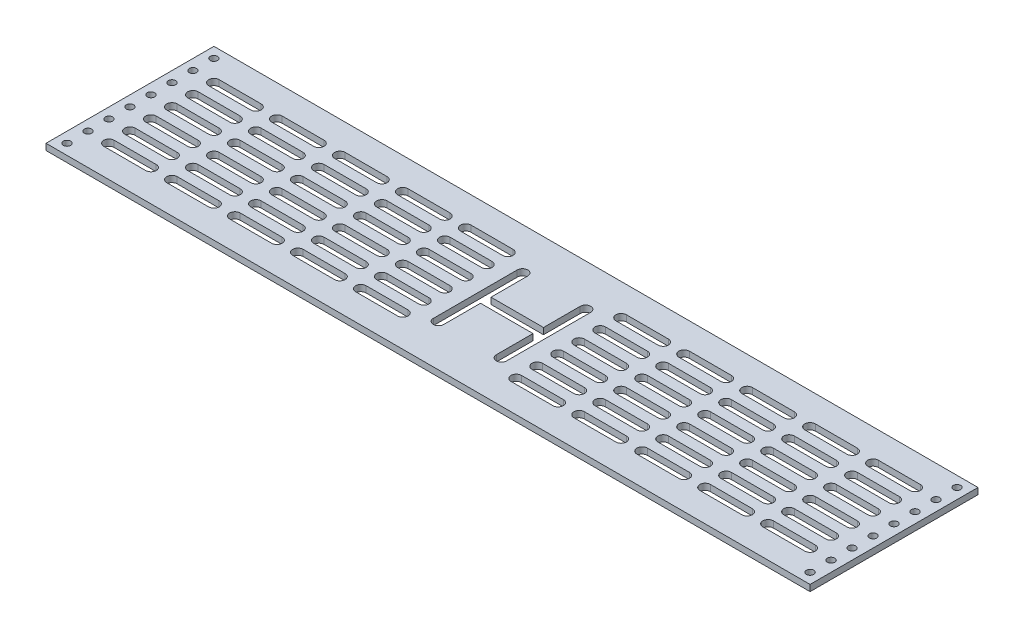
SolidWorks part; units mm, degrees
material "A-玻璃纤维"
ref_plane "前视基准面" through (0, 0, 0) normal (0, 0, 1) x (1, 0, 0)
ref_plane "上视基准面" through (0, 0, 0) normal (0, 1, 0) x (1, 0, 0)
ref_plane "右视基准面" through (0, 0, 0) normal (1, 0, 0) x (0, 0, -1)
other "Configuration Table"
sketch "草图1" plane through (0, 0, 0) normal (0, 1, 0) x (1, 0, 0)
  line L0 (0, 0) -> (-182, 0)
  line L1 (0, 0) -> (182, 0)
  line L2 (182, 0) -> (182, -80)
  line L3 (182, -80) -> (-182, -80)
  line L4 (-182, -80) -> (-182, 0)
extrude "凸台-拉伸1" add sketch "草图1" along normal blind 3
sketch "草图2" plane through (0, 3, 0) normal (0, 1, 0) x (1, 0, 0)
  line L0 (-182, -80) -> (-177, -80)
  line L1 (-182, -80) -> (182, -80) construction
  line L2 (-177, -80) -> (-177, 0)
  line L3 (182, 0) -> (-182, 0) construction
  line L4 (-177, -80) -> (-177, -75)
  line L5 (0, 0) -> (0, -80)
  circle A0 centre (-177, -75) radius 1.75
  circle A1 centre (-177, -65) radius 1.75
  circle A2 centre (-177, -55) radius 1.75
  circle A3 centre (-177, -45) radius 1.75
  circle A4 centre (-177, -35) radius 1.75
  circle A5 centre (-177, -25) radius 1.75
  circle A6 centre (-177, -15) radius 1.75
  circle A7 centre (-177, -5) radius 1.75
  circle A8 centre (177, -5) radius 1.75
  circle A9 centre (177, -15) radius 1.75
  circle A10 centre (177, -25) radius 1.75
  circle A11 centre (177, -35) radius 1.75
  circle A12 centre (177, -45) radius 1.75
  circle A13 centre (177, -55) radius 1.75
  circle A14 centre (177, -65) radius 1.75
  circle A15 centre (177, -75) radius 1.75
  dimension "D1" = 8
  dimension "D2" = 3.5
  dimension "D3" = 5
extrude "切除-拉伸1" cut sketch "草图2" against normal through all contours L4 A0 L2 | L2 A0 L4 | L2 A1 | L2 A1 | L2 A2 | L2 A2 | L2 A3 | L2 A3 | L2 A4 | L2 A4 | L2 A5 | L2 A5 | L2 A6 | L2 A6 | L2 A7 | L2 A7 | A8 | A9 | A10 | A11 | A12 | A13 | A14 | A15
sketch "草图3" plane through (0, 3, 0) normal (0, 1, 0) x (1, 0, 0)
  line L0 (0, 0) -> (0, -80)
  line L1 (182, 0) -> (-182, 0) construction
  line L2 (-182, -80) -> (182, -80) construction
  line L3 (0, -40) -> (-15, -40)
  line L4 (0, -40) -> (15, -40)
  line L5 (15, -40) -> (15, -20)
  line L6 (15, -40) -> (15, -60)
  line L7 (-15, -40) -> (-15, -20)
  line L8 (-15, -40) -> (-15, -60)
  line L9 (-15, -40) -> (15, -40) construction
  line L10 (-12.5, -37.5) -> (12.5, -37.5)
  line L11 (-12.5, -42.5) -> (12.5, -42.5)
  line L12 (-15, -20) -> (-15, -60) construction
  line L13 (-12.5, -20) -> (-12.5, -37.5)
  line L14 (-17.5, -20) -> (-17.5, -60)
  line L15 (15, -20) -> (15, -60) construction
  line L16 (17.5, -20) -> (17.5, -60)
  line L17 (12.5, -20) -> (12.5, -37.5)
  line L18 (12.5, -42.5) -> (12.5, -60)
  line L19 (-12.5, -42.5) -> (-12.5, -60)
  line L20 (-182, -80) -> (0, -80)
  line L21 (-91, -80) -> (-91, 0)
  line L22 (-177, -65) -> (-91, -65)
  line L23 (-177, -65) -> (-167, -65)
  line L24 (-167, -65) -> (-147, -65)
  line L25 (-147, -65) -> (-137, -65)
  line L26 (-137, -65) -> (-117, -65)
  line L27 (-117, -65) -> (-107, -65)
  line L28 (-107, -65) -> (-87, -65)
  line L29 (-87, -65) -> (-77, -65)
  line L30 (-77, -65) -> (-57, -65)
  line L31 (-167, -65) -> (-147, -65) construction
  line L32 (-167, -62.5) -> (-147, -62.5)
  line L33 (-167, -67.5) -> (-147, -67.5)
  line L34 (-137, -65) -> (-117, -65) construction
  line L35 (-137, -62.5) -> (-117, -62.5)
  line L36 (-137, -67.5) -> (-117, -67.5)
  line L37 (-107, -65) -> (-87, -65) construction
  line L38 (-107, -62.5) -> (-87, -62.5)
  line L39 (-107, -67.5) -> (-87, -67.5)
  line L40 (-77, -65) -> (-57, -65) construction
  line L41 (-77, -62.5) -> (-57, -62.5)
  line L42 (-77, -67.5) -> (-57, -67.5)
  line L43 (-167, -57.5) -> (-147, -57.5)
  line L44 (-167, -52.5) -> (-147, -52.5)
  line L45 (-137, -57.5) -> (-117, -57.5)
  line L46 (-137, -52.5) -> (-117, -52.5)
  line L47 (-107, -57.5) -> (-87, -57.5)
  line L48 (-107, -52.5) -> (-87, -52.5)
  line L49 (-77, -57.5) -> (-57, -57.5)
  line L50 (-77, -52.5) -> (-57, -52.5)
  line L51 (-167, -55) -> (-147, -55) construction
  line L52 (-137, -55) -> (-117, -55) construction
  line L53 (-107, -55) -> (-87, -55) construction
  line L54 (-77, -55) -> (-57, -55) construction
  line L55 (-167, -47.5) -> (-147, -47.5)
  line L56 (-167, -42.5) -> (-147, -42.5)
  line L57 (-137, -47.5) -> (-117, -47.5)
  line L58 (-137, -42.5) -> (-117, -42.5)
  line L59 (-107, -47.5) -> (-87, -47.5)
  line L60 (-107, -42.5) -> (-87, -42.5)
  line L61 (-77, -47.5) -> (-57, -47.5)
  line L62 (-77, -42.5) -> (-57, -42.5)
  line L63 (-167, -45) -> (-147, -45) construction
  line L64 (-137, -45) -> (-117, -45) construction
  line L65 (-107, -45) -> (-87, -45) construction
  line L66 (-77, -45) -> (-57, -45) construction
  line L67 (-167, -37.5) -> (-147, -37.5)
  line L68 (-167, -32.5) -> (-147, -32.5)
  line L69 (-137, -37.5) -> (-117, -37.5)
  line L70 (-137, -32.5) -> (-117, -32.5)
  line L71 (-107, -37.5) -> (-87, -37.5)
  line L72 (-107, -32.5) -> (-87, -32.5)
  line L73 (-77, -37.5) -> (-57, -37.5)
  line L74 (-77, -32.5) -> (-57, -32.5)
  line L75 (-167, -35) -> (-147, -35) construction
  line L76 (-137, -35) -> (-117, -35) construction
  line L77 (-107, -35) -> (-87, -35) construction
  line L78 (-77, -35) -> (-57, -35) construction
  line L79 (-167, -27.5) -> (-147, -27.5)
  line L80 (-167, -22.5) -> (-147, -22.5)
  line L81 (-137, -27.5) -> (-117, -27.5)
  line L82 (-137, -22.5) -> (-117, -22.5)
  line L83 (-107, -27.5) -> (-87, -27.5)
  line L84 (-107, -22.5) -> (-87, -22.5)
  line L85 (-77, -27.5) -> (-57, -27.5)
  line L86 (-77, -22.5) -> (-57, -22.5)
  line L87 (-167, -25) -> (-147, -25) construction
  line L88 (-137, -25) -> (-117, -25) construction
  line L89 (-107, -25) -> (-87, -25) construction
  line L90 (-77, -25) -> (-57, -25) construction
  line L91 (-167, -17.5) -> (-147, -17.5)
  line L92 (-167, -12.5) -> (-147, -12.5)
  line L93 (-137, -17.5) -> (-117, -17.5)
  line L94 (-137, -12.5) -> (-117, -12.5)
  line L95 (-107, -17.5) -> (-87, -17.5)
  line L96 (-107, -12.5) -> (-87, -12.5)
  line L97 (-77, -17.5) -> (-57, -17.5)
  line L98 (-77, -12.5) -> (-57, -12.5)
  line L99 (-167, -15) -> (-147, -15) construction
  line L100 (-137, -15) -> (-117, -15) construction
  line L101 (-107, -15) -> (-87, -15) construction
  line L102 (-77, -15) -> (-57, -15) construction
  line L103 (87, -65) -> (77, -65)
  line L104 (107, -65) -> (87, -65)
  line L105 (117, -65) -> (107, -65)
  line L106 (137, -65) -> (117, -65)
  line L107 (147, -65) -> (137, -65)
  line L108 (167, -65) -> (147, -65)
  line L109 (77, -15) -> (57, -15) construction
  line L110 (77, -12.5) -> (57, -12.5)
  line L111 (77, -17.5) -> (57, -17.5)
  line L112 (107, -15) -> (87, -15) construction
  line L113 (107, -12.5) -> (87, -12.5)
  line L114 (107, -17.5) -> (87, -17.5)
  line L115 (137, -15) -> (117, -15) construction
  line L116 (137, -12.5) -> (117, -12.5)
  line L117 (137, -17.5) -> (117, -17.5)
  line L118 (77, -25) -> (57, -25) construction
  line L119 (77, -22.5) -> (57, -22.5)
  line L120 (77, -27.5) -> (57, -27.5)
  line L121 (107, -25) -> (87, -25) construction
  line L122 (107, -22.5) -> (87, -22.5)
  line L123 (107, -27.5) -> (87, -27.5)
  line L124 (137, -25) -> (117, -25) construction
  line L125 (137, -22.5) -> (117, -22.5)
  line L126 (137, -27.5) -> (117, -27.5)
  line L127 (77, -35) -> (57, -35) construction
  line L128 (77, -32.5) -> (57, -32.5)
  line L129 (77, -37.5) -> (57, -37.5)
  line L130 (107, -35) -> (87, -35) construction
  line L131 (107, -32.5) -> (87, -32.5)
  line L132 (107, -37.5) -> (87, -37.5)
  line L133 (137, -35) -> (117, -35) construction
  line L134 (137, -32.5) -> (117, -32.5)
  line L135 (137, -37.5) -> (117, -37.5)
  line L136 (167, -35) -> (147, -35) construction
  line L137 (167, -32.5) -> (147, -32.5)
  line L138 (167, -37.5) -> (147, -37.5)
  line L139 (77, -45) -> (57, -45) construction
  line L140 (77, -42.5) -> (57, -42.5)
  line L141 (77, -47.5) -> (57, -47.5)
  line L142 (107, -45) -> (87, -45) construction
  line L143 (107, -42.5) -> (87, -42.5)
  line L144 (107, -47.5) -> (87, -47.5)
  line L145 (137, -45) -> (117, -45) construction
  line L146 (137, -42.5) -> (117, -42.5)
  line L147 (137, -47.5) -> (117, -47.5)
  line L148 (167, -45) -> (147, -45) construction
  line L149 (167, -42.5) -> (147, -42.5)
  line L150 (167, -47.5) -> (147, -47.5)
  line L151 (77, -55) -> (57, -55) construction
  line L152 (77, -52.5) -> (57, -52.5)
  line L153 (77, -57.5) -> (57, -57.5)
  line L154 (107, -55) -> (87, -55) construction
  line L155 (107, -52.5) -> (87, -52.5)
  line L156 (107, -57.5) -> (87, -57.5)
  line L157 (137, -55) -> (117, -55) construction
  line L158 (137, -52.5) -> (117, -52.5)
  line L159 (137, -57.5) -> (117, -57.5)
  line L160 (167, -55) -> (147, -55) construction
  line L161 (167, -52.5) -> (147, -52.5)
  line L162 (167, -57.5) -> (147, -57.5)
  line L163 (77, -65) -> (57, -65) construction
  line L164 (77, -62.5) -> (57, -62.5)
  line L165 (77, -67.5) -> (57, -67.5)
  line L166 (107, -65) -> (87, -65) construction
  line L167 (107, -62.5) -> (87, -62.5)
  line L168 (107, -67.5) -> (87, -67.5)
  line L169 (137, -65) -> (117, -65) construction
  line L170 (137, -62.5) -> (117, -62.5)
  line L171 (137, -67.5) -> (117, -67.5)
  line L172 (167, -65) -> (147, -65) construction
  line L173 (167, -62.5) -> (147, -62.5)
  line L174 (167, -67.5) -> (147, -67.5)
  line L175 (167, -25) -> (147, -25) construction
  line L176 (167, -22.5) -> (147, -22.5)
  line L177 (167, -27.5) -> (147, -27.5)
  line L178 (167, -15) -> (147, -15) construction
  line L179 (167, -12.5) -> (147, -12.5)
  line L180 (167, -17.5) -> (147, -17.5)
  line L181 (-57, -65) -> (-47, -65)
  line L182 (-47, -65) -> (-27, -65)
  line L183 (-47, -65) -> (-27, -65) construction
  line L184 (-47, -62.5) -> (-27, -62.5)
  line L185 (-47, -67.5) -> (-27, -67.5)
  line L186 (-47, -57.5) -> (-27, -57.5)
  line L187 (-47, -52.5) -> (-27, -52.5)
  line L188 (-47, -55) -> (-27, -55) construction
  line L189 (-47, -47.5) -> (-27, -47.5)
  line L190 (-47, -42.5) -> (-27, -42.5)
  line L191 (-47, -45) -> (-27, -45) construction
  line L192 (-47, -37.5) -> (-27, -37.5)
  line L193 (-47, -32.5) -> (-27, -32.5)
  line L194 (-47, -35) -> (-27, -35) construction
  line L195 (-47, -27.5) -> (-27, -27.5)
  line L196 (-47, -22.5) -> (-27, -22.5)
  line L197 (-47, -25) -> (-27, -25) construction
  line L198 (-47, -17.5) -> (-27, -17.5)
  line L199 (-47, -12.5) -> (-27, -12.5)
  line L200 (-47, -15) -> (-27, -15) construction
  line L201 (47, -65) -> (27, -65)
  line L202 (47, -15) -> (27, -15) construction
  line L203 (47, -12.5) -> (27, -12.5)
  line L204 (47, -17.5) -> (27, -17.5)
  line L205 (47, -25) -> (27, -25) construction
  line L206 (47, -22.5) -> (27, -22.5)
  line L207 (47, -27.5) -> (27, -27.5)
  line L208 (47, -35) -> (27, -35) construction
  line L209 (47, -32.5) -> (27, -32.5)
  line L210 (47, -37.5) -> (27, -37.5)
  line L211 (47, -45) -> (27, -45) construction
  line L212 (47, -42.5) -> (27, -42.5)
  line L213 (47, -47.5) -> (27, -47.5)
  line L214 (47, -55) -> (27, -55) construction
  line L215 (47, -52.5) -> (27, -52.5)
  line L216 (47, -57.5) -> (27, -57.5)
  line L217 (47, -65) -> (27, -65) construction
  line L218 (47, -62.5) -> (27, -62.5)
  line L219 (47, -67.5) -> (27, -67.5)
  arc A2 (-12.5, -20) -> (-17.5, -20) centre (-15, -20) ccw
  arc A3 (-17.5, -60) -> (-12.5, -60) centre (-15, -60) ccw
  arc A4 (17.5, -20) -> (12.5, -20) centre (15, -20) ccw
  arc A5 (12.5, -60) -> (17.5, -60) centre (15, -60) ccw
  arc A6 (-167, -62.5) -> (-167, -67.5) centre (-167, -65) ccw
  arc A7 (-147, -67.5) -> (-147, -62.5) centre (-147, -65) ccw
  arc A8 (-137, -62.5) -> (-137, -67.5) centre (-137, -65) ccw
  arc A9 (-117, -67.5) -> (-117, -62.5) centre (-117, -65) ccw
  arc A10 (-107, -62.5) -> (-107, -67.5) centre (-107, -65) ccw
  arc A11 (-87, -67.5) -> (-87, -62.5) centre (-87, -65) ccw
  arc A12 (-77, -62.5) -> (-77, -67.5) centre (-77, -65) ccw
  arc A13 (-57, -67.5) -> (-57, -62.5) centre (-57, -65) ccw
  arc A14 (-167, -52.5) -> (-167, -57.5) centre (-167, -55) ccw
  arc A15 (-147, -57.5) -> (-147, -52.5) centre (-147, -55) ccw
  arc A16 (-137, -52.5) -> (-137, -57.5) centre (-137, -55) ccw
  arc A17 (-117, -57.5) -> (-117, -52.5) centre (-117, -55) ccw
  arc A18 (-107, -52.5) -> (-107, -57.5) centre (-107, -55) ccw
  arc A19 (-87, -57.5) -> (-87, -52.5) centre (-87, -55) ccw
  arc A20 (-77, -52.5) -> (-77, -57.5) centre (-77, -55) ccw
  arc A21 (-57, -57.5) -> (-57, -52.5) centre (-57, -55) ccw
  arc A22 (-167, -42.5) -> (-167, -47.5) centre (-167, -45) ccw
  arc A23 (-147, -47.5) -> (-147, -42.5) centre (-147, -45) ccw
  arc A24 (-137, -42.5) -> (-137, -47.5) centre (-137, -45) ccw
  arc A25 (-117, -47.5) -> (-117, -42.5) centre (-117, -45) ccw
  arc A26 (-107, -42.5) -> (-107, -47.5) centre (-107, -45) ccw
  arc A27 (-87, -47.5) -> (-87, -42.5) centre (-87, -45) ccw
  arc A28 (-77, -42.5) -> (-77, -47.5) centre (-77, -45) ccw
  arc A29 (-57, -47.5) -> (-57, -42.5) centre (-57, -45) ccw
  arc A30 (-167, -32.5) -> (-167, -37.5) centre (-167, -35) ccw
  arc A31 (-147, -37.5) -> (-147, -32.5) centre (-147, -35) ccw
  arc A32 (-137, -32.5) -> (-137, -37.5) centre (-137, -35) ccw
  arc A33 (-117, -37.5) -> (-117, -32.5) centre (-117, -35) ccw
  arc A34 (-107, -32.5) -> (-107, -37.5) centre (-107, -35) ccw
  arc A35 (-87, -37.5) -> (-87, -32.5) centre (-87, -35) ccw
  arc A36 (-77, -32.5) -> (-77, -37.5) centre (-77, -35) ccw
  arc A37 (-57, -37.5) -> (-57, -32.5) centre (-57, -35) ccw
  arc A38 (-167, -22.5) -> (-167, -27.5) centre (-167, -25) ccw
  arc A39 (-147, -27.5) -> (-147, -22.5) centre (-147, -25) ccw
  arc A40 (-137, -22.5) -> (-137, -27.5) centre (-137, -25) ccw
  arc A41 (-117, -27.5) -> (-117, -22.5) centre (-117, -25) ccw
  arc A42 (-107, -22.5) -> (-107, -27.5) centre (-107, -25) ccw
  arc A43 (-87, -27.5) -> (-87, -22.5) centre (-87, -25) ccw
  arc A44 (-77, -22.5) -> (-77, -27.5) centre (-77, -25) ccw
  arc A45 (-57, -27.5) -> (-57, -22.5) centre (-57, -25) ccw
  arc A46 (-167, -12.5) -> (-167, -17.5) centre (-167, -15) ccw
  arc A47 (-147, -17.5) -> (-147, -12.5) centre (-147, -15) ccw
  arc A48 (-137, -12.5) -> (-137, -17.5) centre (-137, -15) ccw
  arc A49 (-117, -17.5) -> (-117, -12.5) centre (-117, -15) ccw
  arc A50 (-107, -12.5) -> (-107, -17.5) centre (-107, -15) ccw
  arc A51 (-87, -17.5) -> (-87, -12.5) centre (-87, -15) ccw
  arc A52 (-77, -12.5) -> (-77, -17.5) centre (-77, -15) ccw
  arc A53 (-57, -17.5) -> (-57, -12.5) centre (-57, -15) ccw
  arc A54 (77, -12.5) -> (77, -17.5) centre (77, -15) cw
  arc A55 (57, -17.5) -> (57, -12.5) centre (57, -15) cw
  arc A56 (107, -12.5) -> (107, -17.5) centre (107, -15) cw
  arc A57 (87, -17.5) -> (87, -12.5) centre (87, -15) cw
  arc A58 (137, -12.5) -> (137, -17.5) centre (137, -15) cw
  arc A59 (117, -17.5) -> (117, -12.5) centre (117, -15) cw
  arc A60 (77, -22.5) -> (77, -27.5) centre (77, -25) cw
  arc A61 (57, -27.5) -> (57, -22.5) centre (57, -25) cw
  arc A62 (107, -22.5) -> (107, -27.5) centre (107, -25) cw
  arc A63 (87, -27.5) -> (87, -22.5) centre (87, -25) cw
  arc A64 (137, -22.5) -> (137, -27.5) centre (137, -25) cw
  arc A65 (117, -27.5) -> (117, -22.5) centre (117, -25) cw
  arc A66 (77, -32.5) -> (77, -37.5) centre (77, -35) cw
  arc A67 (57, -37.5) -> (57, -32.5) centre (57, -35) cw
  arc A68 (107, -32.5) -> (107, -37.5) centre (107, -35) cw
  arc A69 (87, -37.5) -> (87, -32.5) centre (87, -35) cw
  arc A70 (137, -32.5) -> (137, -37.5) centre (137, -35) cw
  arc A71 (117, -37.5) -> (117, -32.5) centre (117, -35) cw
  arc A72 (167, -32.5) -> (167, -37.5) centre (167, -35) cw
  arc A73 (147, -37.5) -> (147, -32.5) centre (147, -35) cw
  arc A74 (77, -42.5) -> (77, -47.5) centre (77, -45) cw
  arc A75 (57, -47.5) -> (57, -42.5) centre (57, -45) cw
  arc A76 (107, -42.5) -> (107, -47.5) centre (107, -45) cw
  arc A77 (87, -47.5) -> (87, -42.5) centre (87, -45) cw
  arc A78 (137, -42.5) -> (137, -47.5) centre (137, -45) cw
  arc A79 (117, -47.5) -> (117, -42.5) centre (117, -45) cw
  arc A80 (167, -42.5) -> (167, -47.5) centre (167, -45) cw
  arc A81 (147, -47.5) -> (147, -42.5) centre (147, -45) cw
  arc A82 (77, -52.5) -> (77, -57.5) centre (77, -55) cw
  arc A83 (57, -57.5) -> (57, -52.5) centre (57, -55) cw
  arc A84 (107, -52.5) -> (107, -57.5) centre (107, -55) cw
  arc A85 (87, -57.5) -> (87, -52.5) centre (87, -55) cw
  arc A86 (137, -52.5) -> (137, -57.5) centre (137, -55) cw
  arc A87 (117, -57.5) -> (117, -52.5) centre (117, -55) cw
  arc A88 (167, -52.5) -> (167, -57.5) centre (167, -55) cw
  arc A89 (147, -57.5) -> (147, -52.5) centre (147, -55) cw
  arc A90 (77, -62.5) -> (77, -67.5) centre (77, -65) cw
  arc A91 (57, -67.5) -> (57, -62.5) centre (57, -65) cw
  arc A92 (107, -62.5) -> (107, -67.5) centre (107, -65) cw
  arc A93 (87, -67.5) -> (87, -62.5) centre (87, -65) cw
  arc A94 (137, -62.5) -> (137, -67.5) centre (137, -65) cw
  arc A95 (117, -67.5) -> (117, -62.5) centre (117, -65) cw
  arc A96 (167, -62.5) -> (167, -67.5) centre (167, -65) cw
  arc A97 (147, -67.5) -> (147, -62.5) centre (147, -65) cw
  arc A98 (167, -22.5) -> (167, -27.5) centre (167, -25) cw
  arc A99 (147, -27.5) -> (147, -22.5) centre (147, -25) cw
  arc A100 (167, -12.5) -> (167, -17.5) centre (167, -15) cw
  arc A101 (147, -17.5) -> (147, -12.5) centre (147, -15) cw
  arc A102 (-47, -62.5) -> (-47, -67.5) centre (-47, -65) ccw
  arc A103 (-27, -67.5) -> (-27, -62.5) centre (-27, -65) ccw
  arc A104 (-47, -52.5) -> (-47, -57.5) centre (-47, -55) ccw
  arc A105 (-27, -57.5) -> (-27, -52.5) centre (-27, -55) ccw
  arc A106 (-47, -42.5) -> (-47, -47.5) centre (-47, -45) ccw
  arc A107 (-27, -47.5) -> (-27, -42.5) centre (-27, -45) ccw
  arc A108 (-47, -32.5) -> (-47, -37.5) centre (-47, -35) ccw
  arc A109 (-27, -37.5) -> (-27, -32.5) centre (-27, -35) ccw
  arc A110 (-47, -22.5) -> (-47, -27.5) centre (-47, -25) ccw
  arc A111 (-27, -27.5) -> (-27, -22.5) centre (-27, -25) ccw
  arc A112 (-47, -12.5) -> (-47, -17.5) centre (-47, -15) ccw
  arc A113 (-27, -17.5) -> (-27, -12.5) centre (-27, -15) ccw
  arc A114 (47, -12.5) -> (47, -17.5) centre (47, -15) cw
  arc A115 (27, -17.5) -> (27, -12.5) centre (27, -15) cw
  arc A116 (47, -22.5) -> (47, -27.5) centre (47, -25) cw
  arc A117 (27, -27.5) -> (27, -22.5) centre (27, -25) cw
  arc A118 (47, -32.5) -> (47, -37.5) centre (47, -35) cw
  arc A119 (27, -37.5) -> (27, -32.5) centre (27, -35) cw
  arc A120 (47, -42.5) -> (47, -47.5) centre (47, -45) cw
  arc A121 (27, -47.5) -> (27, -42.5) centre (27, -45) cw
  arc A122 (47, -52.5) -> (47, -57.5) centre (47, -55) cw
  arc A123 (27, -57.5) -> (27, -52.5) centre (27, -55) cw
  arc A124 (47, -62.5) -> (47, -67.5) centre (47, -65) cw
  arc A125 (27, -67.5) -> (27, -62.5) centre (27, -65) cw
  point P8 (0, -40)
  point P18 (-15, -40)
  point P23 (15, -40)
  point P43 (-157, -65)
  point P48 (-127, -65)
  point P53 (-97, -65)
  point P58 (-67, -65)
  point P73 (-157, -55)
  point P78 (-127, -55)
  point P83 (-97, -55)
  point P88 (-67, -55)
  point P101 (-157, -45)
  point P106 (-127, -45)
  point P111 (-97, -45)
  point P116 (-67, -45)
  point P129 (-157, -35)
  point P134 (-127, -35)
  point P139 (-97, -35)
  point P144 (-67, -35)
  point P157 (-157, -25)
  point P162 (-127, -25)
  point P167 (-97, -25)
  point P172 (-67, -25)
  point P185 (-157, -15)
  point P190 (-127, -15)
  point P195 (-97, -15)
  point P200 (-67, -15)
  point P212 (67, -15)
  point P219 (97, -15)
  point P226 (127, -15)
  point P233 (67, -25)
  point P240 (97, -25)
  point P247 (127, -25)
  point P254 (67, -35)
  point P261 (97, -35)
  point P268 (127, -35)
  point P275 (157, -35)
  point P282 (67, -45)
  point P289 (97, -45)
  point P296 (127, -45)
  point P303 (157, -45)
  point P310 (67, -55)
  point P317 (97, -55)
  point P324 (127, -55)
  point P331 (157, -55)
  point P337 (67, -65)
  point P342 (97, -65)
  point P347 (127, -65)
  point P352 (157, -65)
  point P359 (157, -25)
  point P366 (157, -15)
  point P374 (-37, -65)
  point P383 (-37, -55)
  point P390 (-37, -45)
  point P397 (-37, -35)
  point P404 (-37, -25)
  point P411 (-37, -15)
  point P418 (37, -15)
  point P425 (37, -25)
  point P432 (37, -35)
  point P439 (37, -45)
  point P446 (37, -55)
  point P451 (37, -65)
  dimension "D3" = 6
  dimension "D4" = 6
  dimension "D1" = 15
  dimension "D2" = 15
extrude "切除-拉伸2" cut sketch "草图3" against normal through all
